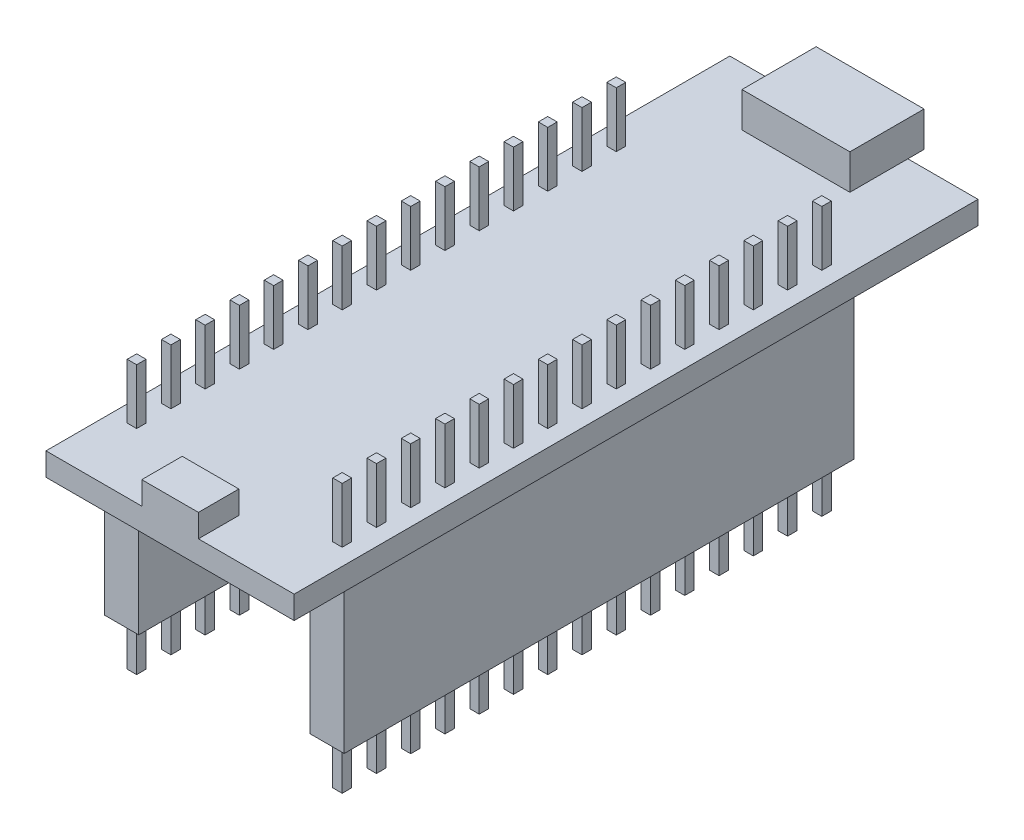
SolidWorks part; units mm, degrees
ref_plane "Plan de face" through (0, 0, 0) normal (0, 0, 1) x (1, 0, 0)
ref_plane "Plan de dessus" through (0, 0, 0) normal (0, 1, 0) x (1, 0, 0)
ref_plane "Plan de droite" through (0, 0, 0) normal (1, 0, 0) x (0, 0, -1)
sketch "Esquisse1" plane through (0, 0, 0) normal (0, 1, 0) x (1, 0, 0)
  line L1 (-9.2, 25.35) -> (9.2, 25.35)
  line L2 (-9.2, 25.35) -> (-9.2, -25.35)
  line L3 (-9.2, -25.35) -> (9.2, -25.35)
  line L4 (9.2, 25.35) -> (9.2, -25.35)
  point P4 (0, 25.35)
  point P6 (-9.2, 0)
  dimension "D1" = 50.7
  dimension "D2" = 18.4
extrude "Boss.-Extru.1" add sketch "Esquisse1" along normal blind 1.7
sketch "Esquisse2" plane through (0, 0, 0) normal (0, 1, 0) x (1, 0, 0)
  line L0 (0, 0) -> (0, 6.2546) construction
  line L1 (9.2, 25.35) -> (-9.2, 25.35) construction
  line L2 (-7.97, 15.7) -> (-7.27, 15.7)
  line L3 (-7.97, 15.7) -> (-7.97, 15)
  line L4 (-7.97, 15) -> (-7.27, 15)
  line L5 (-7.27, 15.7) -> (-7.27, 15)
  line L6 (7.27, 15.7) -> (7.27, 15)
  line L7 (7.97, 15) -> (7.27, 15)
  line L8 (7.97, 15.7) -> (7.97, 15)
  line L9 (7.97, 15.7) -> (7.27, 15.7)
  line L10 (-7.97, 13.16) -> (-7.27, 13.16)
  line L11 (-7.97, 13.16) -> (-7.97, 12.46)
  line L12 (-7.97, 12.46) -> (-7.27, 12.46)
  line L13 (-7.27, 13.16) -> (-7.27, 12.46)
  line L14 (7.27, 13.16) -> (7.27, 12.46)
  line L15 (7.97, 13.16) -> (7.27, 13.16)
  line L16 (7.97, 13.16) -> (7.97, 12.46)
  line L17 (7.97, 12.46) -> (7.27, 12.46)
  line L18 (-7.97, 10.62) -> (-7.27, 10.62)
  line L19 (-7.97, 10.62) -> (-7.97, 9.92)
  line L20 (-7.97, 9.92) -> (-7.27, 9.92)
  line L21 (-7.27, 10.62) -> (-7.27, 9.92)
  line L22 (7.27, 10.62) -> (7.27, 9.92)
  line L23 (7.97, 10.62) -> (7.27, 10.62)
  line L24 (7.97, 10.62) -> (7.97, 9.92)
  line L25 (7.97, 9.92) -> (7.27, 9.92)
  line L26 (-7.97, 8.08) -> (-7.27, 8.08)
  line L27 (-7.97, 8.08) -> (-7.97, 7.38)
  line L28 (-7.97, 7.38) -> (-7.27, 7.38)
  line L29 (-7.27, 8.08) -> (-7.27, 7.38)
  line L30 (7.27, 8.08) -> (7.27, 7.38)
  line L31 (7.97, 8.08) -> (7.27, 8.08)
  line L32 (7.97, 8.08) -> (7.97, 7.38)
  line L33 (7.97, 7.38) -> (7.27, 7.38)
  line L34 (-7.97, 5.54) -> (-7.27, 5.54)
  line L35 (-7.97, 5.54) -> (-7.97, 4.84)
  line L36 (-7.97, 4.84) -> (-7.27, 4.84)
  line L37 (-7.27, 5.54) -> (-7.27, 4.84)
  line L38 (7.27, 5.54) -> (7.27, 4.84)
  line L39 (7.97, 5.54) -> (7.27, 5.54)
  line L40 (7.97, 5.54) -> (7.97, 4.84)
  line L41 (7.97, 4.84) -> (7.27, 4.84)
  line L42 (-7.97, 3) -> (-7.27, 3)
  line L43 (-7.97, 3) -> (-7.97, 2.3)
  line L44 (-7.97, 2.3) -> (-7.27, 2.3)
  line L45 (-7.27, 3) -> (-7.27, 2.3)
  line L46 (7.27, 3) -> (7.27, 2.3)
  line L47 (7.97, 3) -> (7.27, 3)
  line L48 (7.97, 3) -> (7.97, 2.3)
  line L49 (7.97, 2.3) -> (7.27, 2.3)
  line L50 (-7.97, 0.46) -> (-7.27, 0.46)
  line L51 (-7.97, 0.46) -> (-7.97, -0.24)
  line L52 (-7.97, -0.24) -> (-7.27, -0.24)
  line L53 (-7.27, 0.46) -> (-7.27, -0.24)
  line L54 (7.27, 0.46) -> (7.27, -0.24)
  line L55 (7.97, 0.46) -> (7.27, 0.46)
  line L56 (7.97, 0.46) -> (7.97, -0.24)
  line L57 (7.97, -0.24) -> (7.27, -0.24)
  line L58 (-7.97, -2.08) -> (-7.27, -2.08)
  line L59 (-7.97, -2.08) -> (-7.97, -2.78)
  line L60 (-7.97, -2.78) -> (-7.27, -2.78)
  line L61 (-7.27, -2.08) -> (-7.27, -2.78)
  line L62 (7.27, -2.08) -> (7.27, -2.78)
  line L63 (7.97, -2.08) -> (7.27, -2.08)
  line L64 (7.97, -2.08) -> (7.97, -2.78)
  line L65 (7.97, -2.78) -> (7.27, -2.78)
  line L66 (-7.97, -4.62) -> (-7.27, -4.62)
  line L67 (-7.97, -4.62) -> (-7.97, -5.32)
  line L68 (-7.97, -5.32) -> (-7.27, -5.32)
  line L69 (-7.27, -4.62) -> (-7.27, -5.32)
  line L70 (7.27, -4.62) -> (7.27, -5.32)
  line L71 (7.97, -4.62) -> (7.27, -4.62)
  line L72 (7.97, -4.62) -> (7.97, -5.32)
  line L73 (7.97, -5.32) -> (7.27, -5.32)
  line L74 (-7.97, -7.16) -> (-7.27, -7.16)
  line L75 (-7.97, -7.16) -> (-7.97, -7.86)
  line L76 (-7.97, -7.86) -> (-7.27, -7.86)
  line L77 (-7.27, -7.16) -> (-7.27, -7.86)
  line L78 (7.27, -7.16) -> (7.27, -7.86)
  line L79 (7.97, -7.16) -> (7.27, -7.16)
  line L80 (7.97, -7.16) -> (7.97, -7.86)
  line L81 (7.97, -7.86) -> (7.27, -7.86)
  line L82 (-7.97, -9.7) -> (-7.27, -9.7)
  line L83 (-7.97, -9.7) -> (-7.97, -10.4)
  line L84 (-7.97, -10.4) -> (-7.27, -10.4)
  line L85 (-7.27, -9.7) -> (-7.27, -10.4)
  line L86 (7.27, -9.7) -> (7.27, -10.4)
  line L87 (7.97, -9.7) -> (7.27, -9.7)
  line L88 (7.97, -9.7) -> (7.97, -10.4)
  line L89 (7.97, -10.4) -> (7.27, -10.4)
  line L90 (-7.97, -12.24) -> (-7.27, -12.24)
  line L91 (-7.97, -12.24) -> (-7.97, -12.94)
  line L92 (-7.97, -12.94) -> (-7.27, -12.94)
  line L93 (-7.27, -12.24) -> (-7.27, -12.94)
  line L94 (7.27, -12.24) -> (7.27, -12.94)
  line L95 (7.97, -12.24) -> (7.27, -12.24)
  line L96 (7.97, -12.24) -> (7.97, -12.94)
  line L97 (7.97, -12.94) -> (7.27, -12.94)
  line L98 (-7.97, -14.78) -> (-7.27, -14.78)
  line L99 (-7.97, -14.78) -> (-7.97, -15.48)
  line L100 (-7.97, -15.48) -> (-7.27, -15.48)
  line L101 (-7.27, -14.78) -> (-7.27, -15.48)
  line L102 (7.27, -14.78) -> (7.27, -15.48)
  line L103 (7.97, -14.78) -> (7.27, -14.78)
  line L104 (7.97, -14.78) -> (7.97, -15.48)
  line L105 (7.97, -15.48) -> (7.27, -15.48)
  line L106 (-7.97, -17.32) -> (-7.27, -17.32)
  line L107 (-7.97, -17.32) -> (-7.97, -18.02)
  line L108 (-7.97, -18.02) -> (-7.27, -18.02)
  line L109 (-7.27, -17.32) -> (-7.27, -18.02)
  line L110 (7.27, -17.32) -> (7.27, -18.02)
  line L111 (7.97, -17.32) -> (7.27, -17.32)
  line L112 (7.97, -17.32) -> (7.97, -18.02)
  line L113 (7.97, -18.02) -> (7.27, -18.02)
  line L114 (-7.97, -19.86) -> (-7.27, -19.86)
  line L115 (-7.97, -19.86) -> (-7.97, -20.56)
  line L116 (-7.97, -20.56) -> (-7.27, -20.56)
  line L117 (-7.27, -19.86) -> (-7.27, -20.56)
  line L118 (7.27, -19.86) -> (7.27, -20.56)
  line L119 (7.97, -19.86) -> (7.27, -19.86)
  line L120 (7.97, -19.86) -> (7.97, -20.56)
  line L121 (7.97, -20.56) -> (7.27, -20.56)
  point P5 (-7.27, 15.35)
  point P14 (-7.62, 15.7)
  point P15 (7.62, 15.7)
  dimension "D1" = 0.7
  dimension "D2" = 10
  dimension "D3" = 15.24
  dimension "D4" = 15
extrude "Boss.-Extru.2" add sketch "Esquisse2" against normal blind 14.1 and the other way blind 5.8
sketch "Esquisse3" plane through (0, 0, 0) normal (0, 1, 0) x (1, 0, 0)
  line L0 (0, 0) -> (0, 2.8247) construction
  line L1 (-8.89, 16.47) -> (-6.35, 16.47)
  line L2 (-8.89, 16.47) -> (-8.89, -21.33)
  line L3 (-8.89, -21.33) -> (-6.35, -21.33)
  line L4 (-6.35, 16.47) -> (-6.35, -21.33)
  line L5 (6.35, 16.47) -> (6.35, -21.33)
  line L6 (8.89, -21.33) -> (6.35, -21.33)
  line L7 (8.89, 16.47) -> (8.89, -21.33)
  line L8 (8.89, 16.47) -> (6.35, 16.47)
  line L9 (-7.97, 15.7) -> (-7.27, 15.7) construction
  line L10 (-7.97, -2.78) -> (-7.97, -2.08) construction
  point P13 (-7.62, 15.7)
  point P14 (-7.62, 16.47)
  point P18 (-7.97, -2.43)
  point P19 (-8.89, -2.43)
  dimension "D1" = 37.8
  dimension "D2" = 2.54
extrude "Boss.-Extru.3" add sketch "Esquisse3" against normal blind 10.7
sketch "Esquisse4" plane through (0, 1.7, 0) normal (0, 1, 0) x (1, 0, 0)
  line L0 (9.2, 25.35) -> (-9.2, 25.35) construction
  line L1 (-4, 26.55) -> (4, 26.55)
  line L2 (-4, 26.55) -> (-4, 21.05)
  line L3 (-4, 21.05) -> (4, 21.05)
  line L4 (4, 26.55) -> (4, 21.05)
  point P6 (0, 21.05)
  dimension "D1" = 5.5
  dimension "D2" = 8
  dimension "D3" = 1.2
extrude "Boss.-Extru.4" add sketch "Esquisse4" along normal blind 2.6
sketch "Esquisse5" plane through (0, 1.7, 0) normal (0, 1, 0) x (1, 0, 0)
  line L0 (-9.2, -25.35) -> (9.2, -25.35) construction
  line L1 (-2.1, -25.35) -> (2.1, -25.35)
  line L2 (-2.1, -25.35) -> (-2.1, -22.35)
  line L3 (-2.1, -22.35) -> (2.1, -22.35)
  line L4 (2.1, -25.35) -> (2.1, -22.35)
  point P6 (0, -22.35)
  dimension "D1" = 4.2
  dimension "D2" = 3
extrude "Boss.-Extru.5" add sketch "Esquisse5" along normal blind 1.7
